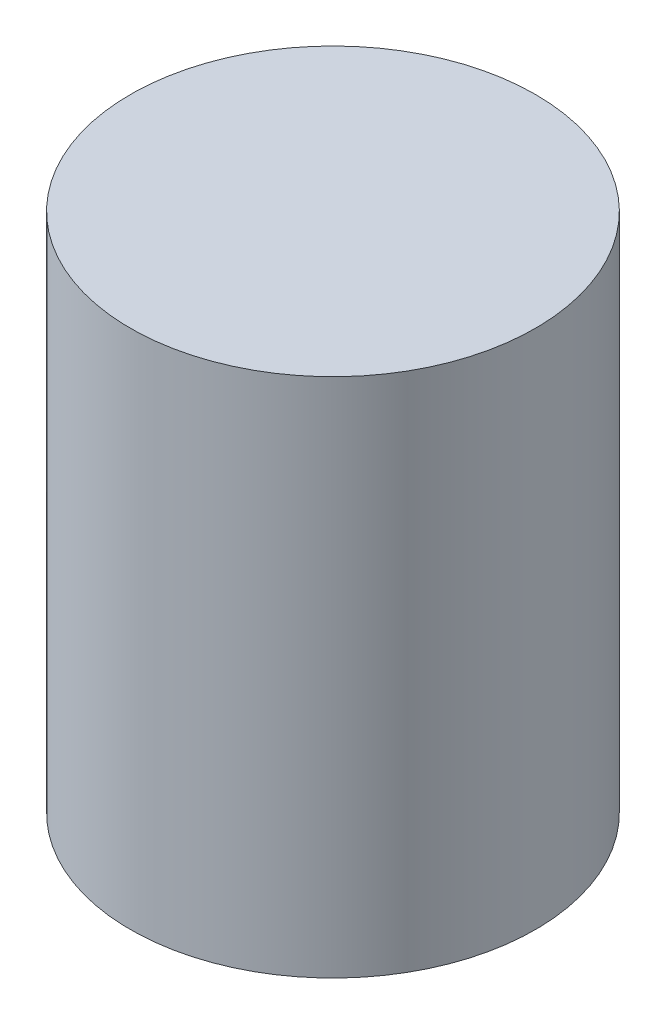
SolidWorks part; units mm, degrees
ref_plane "Front Plane" through (0, 0, 0) normal (0, 0, 1) x (1, 0, 0)
ref_plane "Top Plane" through (0, 0, 0) normal (0, 1, 0) x (1, 0, 0)
ref_plane "Right Plane" through (0, 0, 0) normal (1, 0, 0) x (0, 0, -1)
sketch "Sketch1" plane through (0, 0, 0) normal (0, 1, 0) x (1, 0, 0)
  circle A0 centre (0, 0) radius 70
  dimension "D1" = 140
extrude "Boss-Extrude1" add sketch "Sketch1" along normal blind 180
